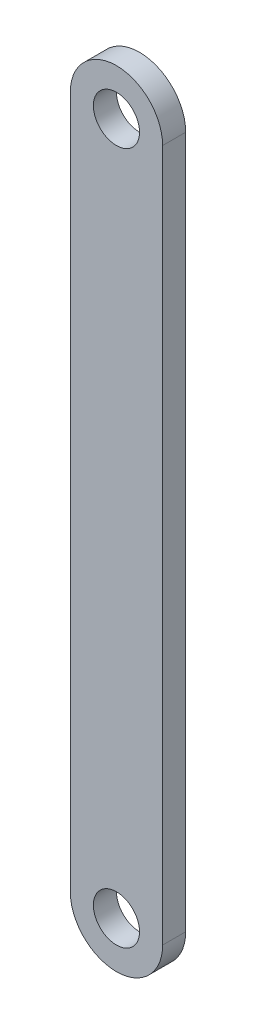
SolidWorks part; units mm, degrees
material "5052-H32"
ref_plane "Front Plane" through (0, 0, 0) normal (0, 0, 1) x (1, 0, 0)
ref_plane "Top Plane" through (0, 0, 0) normal (0, 1, 0) x (1, 0, 0)
ref_plane "Right Plane" through (0, 0, 0) normal (1, 0, 0) x (0, 0, -1)
sketch "Sketch1" plane through (0, 0, 0) normal (0, 0, 1) x (1, 0, 0)
  line L0 (-25.4, -381) -> (-25.4, 0)
  line L1 (25.4, 0) -> (25.4, -381)
  arc A0 (25.4, 0) -> (-25.4, 0) centre (0, 0) ccw
  arc A1 (-25.4, -381) -> (25.4, -381) centre (0, -381) ccw
  circle A2 centre (0, 0) radius 12.7
  circle A3 centre (0, -381) radius 12.7
  dimension "D1" = 25.4
  dimension "D3" = 25.4
  dimension "D4" = 25.4
  dimension "D5" = 25.4
  dimension "D2" = 381
extrude "Boss-Extrude1" add sketch "Sketch1" along normal blind 12.7
